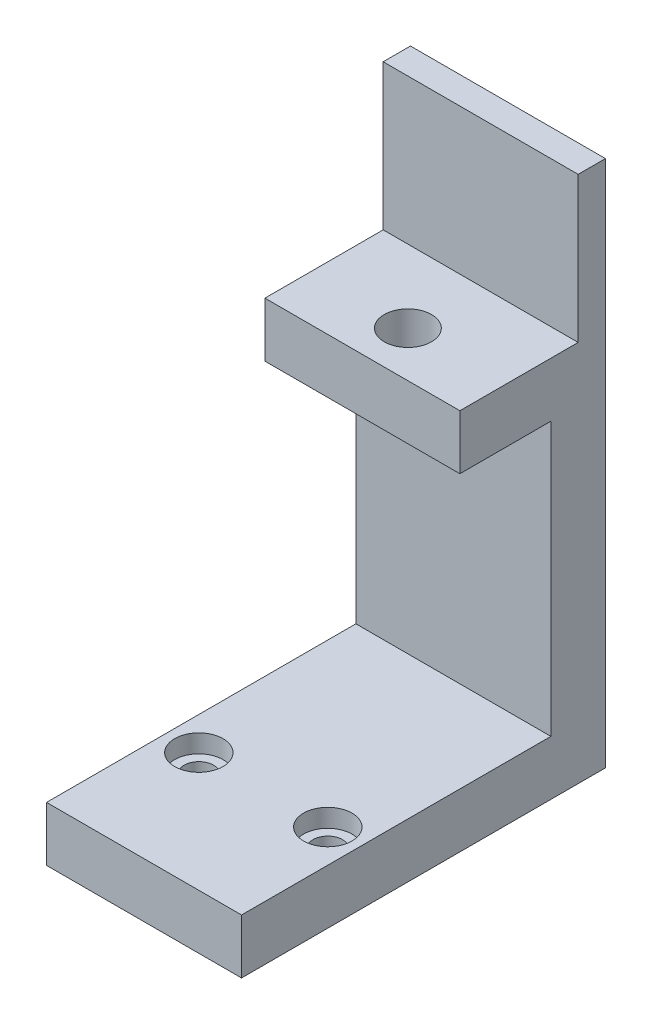
SolidWorks part; units mm, degrees
ref_plane "Front Plane" through (0, 0, 0) normal (0, 0, 1) x (1, 0, 0)
ref_plane "Top Plane" through (0, 0, 0) normal (0, 1, 0) x (1, 0, 0)
ref_plane "Right Plane" through (0, 0, 0) normal (1, 0, 0) x (0, 0, -1)
sketch "Sketch1" plane through (0, 0, 0) normal (0, 1, 0) x (1, 0, 0)
  line L1 (-13.9568, 42.3827) -> (13.2632, 42.3827)
  line L2 (-13.9568, 42.3827) -> (-13.9568, -8.4173)
  line L3 (-13.9568, -8.4173) -> (13.2632, -8.4173)
  line L4 (13.2632, 42.3827) -> (13.2632, -8.4173)
  dimension "D1" = 50.8
  dimension "D2" = 27.22
extrude "Boss-Extrude1" add sketch "Sketch1" along normal blind 7.62
sketch "Sketch2" plane through (0, 7.62, 0) normal (0, 1, 0) x (1, 0, 0)
  line L0 (-13.9568, 42.3827) -> (-13.9568, -8.4173) construction
  line L1 (-13.9568, -8.4173) -> (13.2632, -8.4173) construction
  circle A0 centre (-9.3468, 8.2327) radius 2.05
  point P0 (-9.3468, 8.2327)
  dimension "D1" = 4.61
  dimension "D2" = 16.65
extrude "Cut-Extrude1" cut sketch "Sketch2" against normal blind 7.62 contours A0
sketch "Sketch3" plane through (0, 7.62, 0) normal (0, 1, 0) x (1, 0, 0)
  circle A0 centre (-9.3468, 8.2327) radius 3.3782
  point P0 (-9.3468, 8.2327)
extrude "Cut-Extrude2" cut sketch "Sketch3" against normal blind 2.54
ref_plane "Plane1" through (-0.3468, 0, 0) normal (-1, 0, 0) x (0, 0, 1)
mirror "Mirror1" about plane through (-0.3468, 0, 0) normal (-1, 0, 0) of "Cut-Extrude2", "Cut-Extrude1"
sketch "Sketch4" plane through (0, 7.62, 0) normal (0, 1, 0) x (1, 0, 0)
  line L0 (13.2632, -8.4173) -> (13.2632, 42.3827) construction
  line L1 (-13.9568, 42.3827) -> (13.2632, 42.3827)
  line L2 (-13.9568, 42.3827) -> (-13.9568, 34.7627)
  line L3 (-13.9568, 34.7627) -> (13.2632, 34.7627)
  line L4 (13.2632, 42.3827) -> (13.2632, 34.7627)
  dimension "D1" = 7.62
extrude "Boss-Extrude2" add sketch "Sketch4" along normal blind 45.72
sketch "Sketch10" plane through (0, 0, -34.7627) normal (0, 0, 1) x (1, 0, 0)
  line L0 (-13.9568, 53.34) -> (-13.9568, 7.62) construction
  line L1 (13.2632, 53.34) -> (-13.9568, 53.34)
  line L2 (13.2632, 53.34) -> (13.2632, 45.72)
  line L3 (13.2632, 45.72) -> (-13.9568, 45.72)
  line L4 (-13.9568, 53.34) -> (-13.9568, 45.72)
  dimension "D1" = 7.62
extrude "Boss-Extrude3" add sketch "Sketch10" along normal blind 12.7
sketch "Sketch11" plane through (0, 45.72, 0) normal (0, -1, 0) x (1, 0, 0)
  line L0 (-0.3468, -22.0627) -> (-0.3468, -34.7627)
  line L1 (-13.9568, -22.0627) -> (13.2632, -22.0627) construction
  line L2 (-13.9568, -34.7627) -> (13.2632, -34.7627) construction
  circle A0 centre (-0.3468, -28.4127) radius 3.302
extrude "Cut-Extrude6" cut sketch "Sketch11" against normal blind 7.62 contours L0 A0
sketch "Sketch13" plane through (0, 45.72, 0) normal (0, -1, 0) x (1, 0, 0)
  circle A0 centre (-0.3468, -28.4127) radius 4.826
extrude "Cut-Extrude7" cut sketch "Sketch13" against normal blind 2.54
sketch "Sketch12" plane through (0, 53.34, 0) normal (0, 1, 0) x (1, 0, 0)
  line L0 (13.2632, 22.0627) -> (13.2632, 42.3827) construction
  line L1 (-13.9568, 42.3827) -> (13.2632, 42.3827)
  line L2 (-13.9568, 42.3827) -> (-13.9568, 38.5727)
  line L3 (-13.9568, 38.5727) -> (13.2632, 38.5727)
  line L4 (13.2632, 42.3827) -> (13.2632, 38.5727)
  dimension "D1" = 3.81
extrude "Boss-Extrude4" add sketch "Sketch12" along normal blind 20.32
